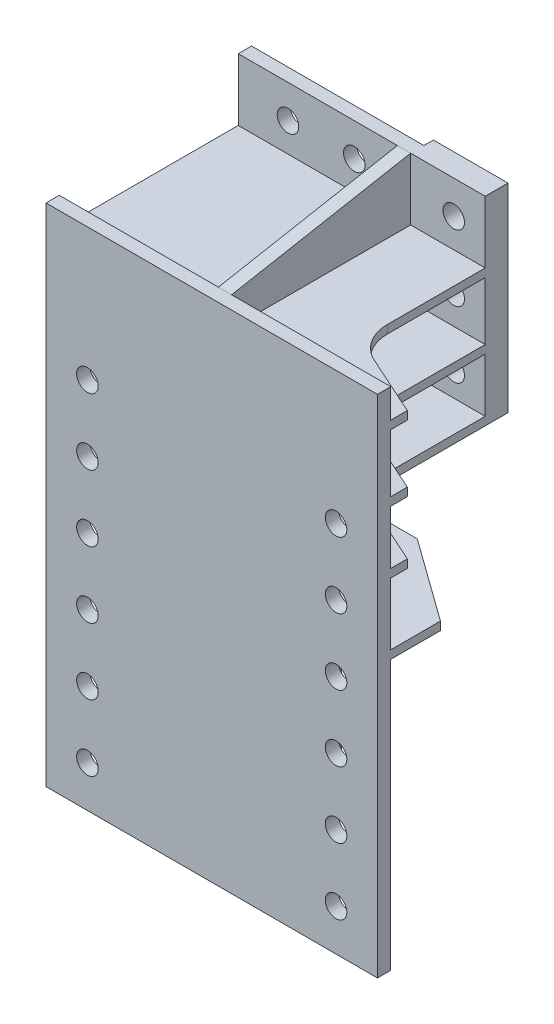
SolidWorks part; units mm, degrees
ref_plane "前视基准面" through (0, 0, 0) normal (0, 0, 1) x (1, 0, 0)
ref_plane "上视基准面" through (0, 0, 0) normal (0, 1, 0) x (1, 0, 0)
ref_plane "右视基准面" through (0, 0, 0) normal (1, 0, 0) x (0, 0, -1)
sketch "草图1" plane through (0, 0, 0) normal (0, 0, 1) x (1, 0, 0)
  line L1 (0, 0) -> (400, 0)
  line L2 (0, 0) -> (0, 610)
  line L3 (0, 610) -> (400, 610)
  line L4 (400, 0) -> (400, 610)
  dimension "D1" = 400
  dimension "D2" = 610
extrude "凸台-拉伸1" add sketch "草图1" along normal blind 16
sketch "草图2" plane through (0, 0, 16) normal (0, 0, 1) x (1, 0, 0)
  line L0 (0, 610) -> (0, 0) construction
  line L1 (0, 0) -> (400, 0) construction
  circle A0 centre (50, 50) radius 13
  dimension "D3" = 26
  dimension "D1" = 50
  dimension "D2" = 50
extrude "切除-拉伸1" cut sketch "草图2" against normal through all
pattern_linear "阵列(线性)1" count 2 spacing 300 along (1, 0, 0) count 6 spacing 80 along (0, 1, 0) of "切除-拉伸1"
sketch "草图3" plane through (0, 0, 16) normal (0, 0, 1) x (1, 0, 0)
  line L0 (200, -390) -> (200, 49610) construction
  line L1 (400, 610) -> (0, 610) construction
  line L2 (0, 0) -> (400, 0) construction
  line L3 (192, 0) -> (208, 0)
  line L4 (192, 0) -> (192, 650)
  line L5 (192, 650) -> (208, 650)
  line L6 (208, 0) -> (208, 650)
  point P5 (200, 610)
  dimension "D1" = 650
  dimension "D2" = 16
extrude "凸台-拉伸2" add sketch "草图3" along normal blind 216
sketch "草图4" plane through (208, 0, 0) normal (1, 0, 0) x (0, 0, -1)
  line L0 (-232, 650) -> (-16, 650)
  line L1 (-16, 650) -> (-16, 610)
  line L2 (-16, 610) -> (-232, 650)
  line L3 (-198.5, 410) -> (-232, 410)
  line L4 (-232, 0) -> (-232, 650) construction
  line L5 (-232, 410) -> (-232, 0)
  line L6 (-232, 0) -> (-148.5, 0)
  line L7 (-232, 0) -> (-16, 0) construction
  line L8 (-148.5, 0) -> (-148.5, 360)
  line L9 (-16, 0) -> (-16, 610) construction
  arc A0 (-198.5, 410) -> (-148.5, 360) centre (-198.5, 360) cw
  circle A1 centre (-93.5, 210) radius 13
  circle A2 centre (-93.5, 130) radius 13
  circle A3 centre (-93.5, 50) radius 13
  dimension "D3" = 50
  dimension "D4" = 26
  dimension "D1" = 240
  dimension "D2" = 132.5
  dimension "D5" = 50
  dimension "D6" = 80
  dimension "D7" = 80
  dimension "D8" = 138.5
extrude "切除-拉伸2" cut sketch "草图4" against normal through all
sketch "草图5" plane through (0, 0, 16) normal (0, 0, 1) x (1, 0, 0)
  line L0 (0, 610) -> (0, 0) construction
  line L1 (0, 575) -> (400, 575)
  line L2 (0, 575) -> (0, 565)
  line L3 (0, 565) -> (400, 565)
  line L4 (400, 575) -> (400, 565)
  line L5 (400, 0) -> (400, 610) construction
  line L6 (400, 610) -> (208, 610) construction
  line L7 (0, 495) -> (400, 495)
  line L8 (0, 495) -> (0, 485)
  line L9 (0, 485) -> (400, 485)
  line L10 (400, 495) -> (400, 485)
  line L11 (0, 420) -> (400, 420)
  line L12 (0, 420) -> (0, 410)
  line L13 (0, 410) -> (400, 410)
  line L14 (400, 420) -> (400, 410)
  dimension "D1" = 10
  dimension "D2" = 10
  dimension "D3" = 10
  dimension "D4" = 35
  dimension "D5" = 80
  dimension "D6" = 75
extrude "凸台-拉伸3" add sketch "草图5" along normal blind 216
sketch "草图6" plane through (0, 410, 0) normal (0, -1, 0) x (-1, 0, 0)
  line L0 (-298, -232) -> (-298, -114.3004)
  line L1 (0, -232) -> (-400, -232) construction
  line L2 (-327.4446, -68.7211) -> (-400, -36)
  line L3 (-400, -232) -> (-400, -16) construction
  line L4 (-400, -36) -> (-400, -232)
  line L5 (-400, -232) -> (-298, -232)
  line L6 (-208, -148.5) -> (-208, -16) construction
  line L7 (-208, -16) -> (-400, -16) construction
  line L8 (-208, -16) -> (-400, -16) construction
  arc A0 (-327.4446, -68.7211) -> (-298, -114.3004) centre (-348, -114.3004) cw
  point P17 (-298, -82)
  dimension "D4" = 50
  dimension "D1" = 90
  dimension "D2" = 20
  dimension "D3" = 66
extrude "切除-拉伸3" cut sketch "草图6" against normal through all
sketch "草图7" plane through (0, 0, 16) normal (0, 0, 1) x (1, 0, 0)
  line L0 (0, 410) -> (0, 0) construction
  line L1 (0, 335) -> (400, 335)
  line L2 (0, 335) -> (0, 325)
  line L3 (0, 325) -> (400, 325)
  line L4 (400, 335) -> (400, 325)
  line L5 (400, 0) -> (400, 410) construction
  line L6 (192, 420) -> (0, 420) construction
  dimension "D1" = 85
  dimension "D2" = 10
extrude "凸台-拉伸4" add sketch "草图7" along normal blind 132
sketch "草图8" plane through (0, 325, 0) normal (0, -1, 0) x (-1, 0, 0)
  line L0 (-400, -148) -> (-300, -148)
  line L1 (-208, -148) -> (-400, -148) construction
  line L2 (-300, -148) -> (-400, -76)
  line L3 (-400, -148) -> (-400, -16) construction
  line L4 (-400, -76) -> (-400, -148)
  line L5 (-208, -16) -> (-400, -16) construction
  line L6 (0, -148) -> (-100, -148)
  line L7 (0, -148) -> (-192, -148) construction
  line L8 (-100, -148) -> (0, -76)
  line L9 (0, -148) -> (0, -16) construction
  line L10 (0, -76) -> (0, -148)
  dimension "D1" = 100
  dimension "D2" = 60
extrude "切除-拉伸4" cut sketch "草图8" against normal blind 10
sketch "草图9" plane through (0, 0, 232) normal (0, 0, 1) x (1, 0, 0)
  line L0 (208, 650) -> (192, 650) construction
  line L1 (0, 650) -> (298, 650)
  line L2 (0, 650) -> (0, 410)
  line L3 (0, 410) -> (298, 410)
  line L4 (298, 650) -> (298, 410)
  line L5 (0, 565) -> (0, 495) construction
  dimension "D1" = 240
  dimension "D2" = 298
extrude "凸台-拉伸5" add sketch "草图9" along normal blind 16
sketch "草图10" plane through (0, 0, 248) normal (0, 0, 1) x (1, 0, 0)
  line L0 (0, 650) -> (0, 410) construction
  line L1 (298, 650) -> (0, 650) construction
  circle A0 centre (60, 610) radius 13
  dimension "D1" = 26
  dimension "D2" = 60
  dimension "D3" = 40
extrude "切除-拉伸5" cut sketch "草图10" against normal blind 16
pattern_linear "阵列(线性)2" count 2 spacing 80 along (1, 0, 0) of "切除-拉伸5"
pattern_linear "阵列(线性)3" count 2 spacing 200 along (1, 0, 0) of "切除-拉伸5"
pattern_linear "阵列(线性)4" count 3 spacing 80 along (0, -1, 0) of "切除-拉伸5", "阵列(线性)2", "阵列(线性)3"
sketch "草图12" plane through (0, 0, 248) normal (0, 0, 1) x (1, 0, 0)
  line L0 (208, 410) -> (400, 410) construction
  line L1 (298, 410) -> (208, 410)
  line L2 (298, 410) -> (298, 650)
  line L3 (298, 650) -> (208, 650)
  line L4 (208, 410) -> (208, 650)
  line L5 (298, 410) -> (298, 650) construction
  line L6 (298, 650) -> (0, 650) construction
  line L7 (208, 335) -> (208, 410) construction
  circle A0 centre (260, 610) radius 13
  circle A1 centre (260, 530) radius 13
  circle A2 centre (260, 450) radius 13
  circle A3 centre (260, 450) radius 13 construction
  circle A4 centre (260, 530) radius 13 construction
  circle A5 centre (260, 610) radius 13 construction
extrude "凸台-拉伸6" add sketch "草图12" along normal blind 11.5
mirror "镜向1" about plane through (0, 0, 0) normal (0, 0, 1) of bodies 125 119
sketch "草图11" plane through (0, 0, 0) normal (-1, 0, 0) x (0, 0, 1)
  line L1 (0, 0) -> (259.5, 0)
  line L2 (0, 0) -> (0, 650)
  line L3 (0, 650) -> (259.5, 650)
  line L4 (259.5, 0) -> (259.5, 650)
extrude "切除-拉伸6" cut sketch "草图11" against normal through all
